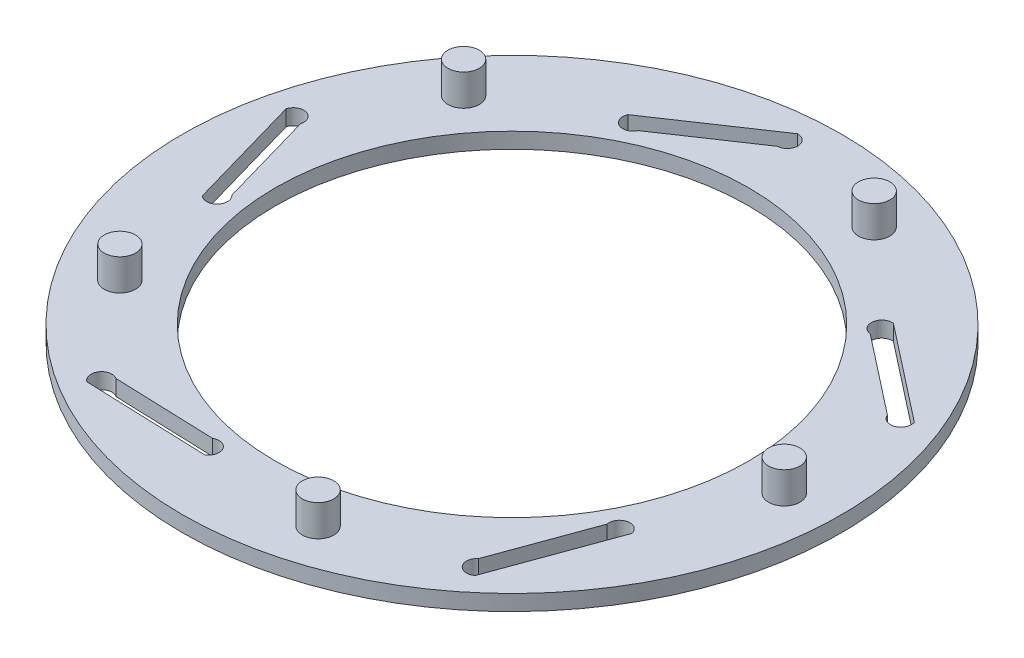
SolidWorks part; units mm, degrees
ref_plane "Front Plane" through (0, 0, 0) normal (0, 0, 1) x (1, 0, 0)
ref_plane "Top Plane" through (0, 0, 0) normal (0, 1, 0) x (1, 0, 0)
ref_plane "Right Plane" through (0, 0, 0) normal (1, 0, 0) x (0, 0, -1)
sketch "Sketch1" plane through (0, 0, 0) normal (0, 1, 0) x (1, 0, 0)
  line L0 (0, -41.439) -> (0, 59.5224) construction
  line L1 (-42.487, -10.5704) -> (53.5331, 20.6284) construction
  line L2 (-26.2584, 39.3761) -> (33.0853, -42.3035) construction
  line L3 (26.2584, 39.3761) -> (-33.0853, -42.3035) construction
  line L4 (42.487, -10.5704) -> (-53.5331, 20.6284) construction
  line L5 (0, 3.2345) -> (0, -41.439) construction
  line L6 (25.4456, 10.4371) -> (17.9073, 16.3345)
  line L7 (-11.8214, 22.9078) -> (-2.1477, 29.4237)
  line L8 (-2.0632, 27.4255) -> (-10.0014, 22.0785)
  line L9 (18.1336, 18.3217) -> (27.3199, 11.135)
  line L10 (17.7894, -20.975) -> (21.0687, -11.9832)
  line L11 (23.0286, -11.5844) -> (19.0324, -22.5418)
  line L12 (-14.4511, -23.4004) -> (-4.8861, -23.7406)
  line L13 (-3.9012, -25.4812) -> (-15.5572, -25.0667)
  line L14 (-26.7207, 6.5127) -> (-24.0885, -2.6893)
  line L15 (-25.4396, -4.1639) -> (-28.6473, 7.0498)
  circle A0 centre (0, 0) radius 31.5
  circle A1 centre (0, 0) radius 22.625
  arc A4 (-11.8214, 22.9078) -> (-10.0014, 22.0785) centre (-10.9114, 22.4931) ccw
  arc A5 (-2.1477, 29.4237) -> (-2.0632, 27.4255) centre (-2.1055, 28.4246) cw
  arc A54 (18.1336, 18.3217) -> (17.9073, 16.3345) centre (18.0204, 17.3281) ccw
  arc A55 (27.3199, 11.135) -> (25.4456, 10.4371) centre (26.3827, 10.7861) cw
  arc A56 (23.0286, -11.5844) -> (21.0687, -11.9832) centre (22.0486, -11.7838) ccw
  arc A57 (19.0324, -22.5418) -> (17.7894, -20.975) centre (18.4109, -21.7584) cw
  arc A58 (-3.9012, -25.4812) -> (-4.8861, -23.7406) centre (-4.3936, -24.6109) ccw
  arc A59 (-15.5572, -25.0667) -> (-14.4511, -23.4004) centre (-15.0042, -24.2335) cw
  arc A60 (-25.4396, -4.1639) -> (-24.0885, -2.6893) centre (-24.7641, -3.4266) ccw
  arc A61 (-28.6473, 7.0498) -> (-26.7207, 6.5127) centre (-27.684, 6.7813) cw
  point P4 (0, 24.1)
  point P50 (0, 0)
  dimension "D1" = 63
  dimension "D2" = 45.25
  dimension "D3" = 24.1
  dimension "D4" = 5
  dimension "D5" = 44.6735
  dimension "D6" = 28.5024
  dimension "D8" = 5
  dimension "D11" = 25
  dimension "D7" = 2
  dimension "D9" = 29.4237
extrude "Boss-Extrude1" add sketch "Sketch1" along normal blind 1.5
sketch "Sketch2" plane through (0, 1.5, 0) normal (0, 1, 0) x (1, 0, 0)
  line L0 (0, 0) -> (-21.2646, 16.6378) construction
  circle A0 centre (-21.2646, 16.6378) radius 1.5
  circle A1 centre (0, 0) radius 22.625 construction
  circle A2 centre (9.2523, 25.3652) radius 1.5
  circle A3 centre (26.9829, -0.9612) radius 1.5
  circle A4 centre (7.424, -25.9593) radius 1.5
  circle A5 centre (-22.3946, -15.0825) radius 1.5
  point P0 (-21.2646, 16.6378)
  dimension "D1" = 3
  dimension "D2" = 27
  dimension "D4" = 27
  dimension "D3" = 5
extrude "Boss-Extrude2" add sketch "Sketch2" along normal blind 3
